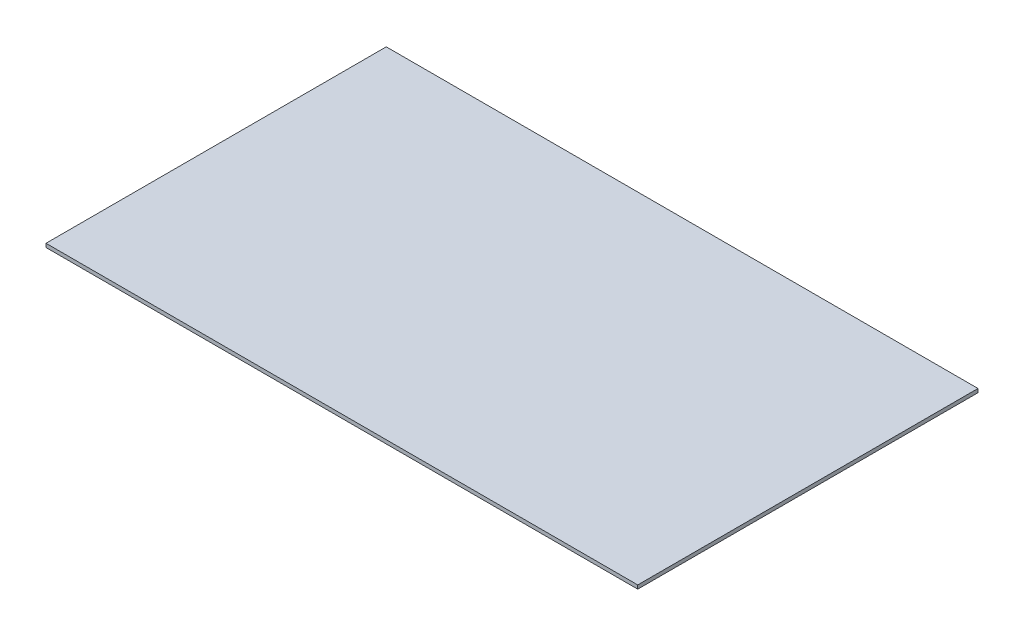
SolidWorks part; units mm, degrees
ref_plane "Front Plane" through (0, 0, 0) normal (0, 0, 1) x (1, 0, 0)
ref_plane "Top Plane" through (0, 0, 0) normal (0, 1, 0) x (1, 0, 0)
ref_plane "Right Plane" through (0, 0, 0) normal (1, 0, 0) x (0, 0, -1)
sketch "Sketch2" plane through (0, 0, 0) normal (0, 1, 0) x (1, 0, 0)
  line L1 (-254, -146.05) -> (254, -146.05)
  line L2 (-254, -146.05) -> (-254, 146.05)
  line L3 (-254, 146.05) -> (254, 146.05)
  line L4 (254, -146.05) -> (254, 146.05)
  line L5 (-254, -146.05) -> (254, 146.05) construction
  line L6 (-254, 146.05) -> (254, -146.05) construction
  point P0 (0, 0)
  dimension "D1" = 508
  dimension "D2" = 292.1
extrude "Boss-Extrude1" add sketch "Sketch2" along normal blind 3.175
